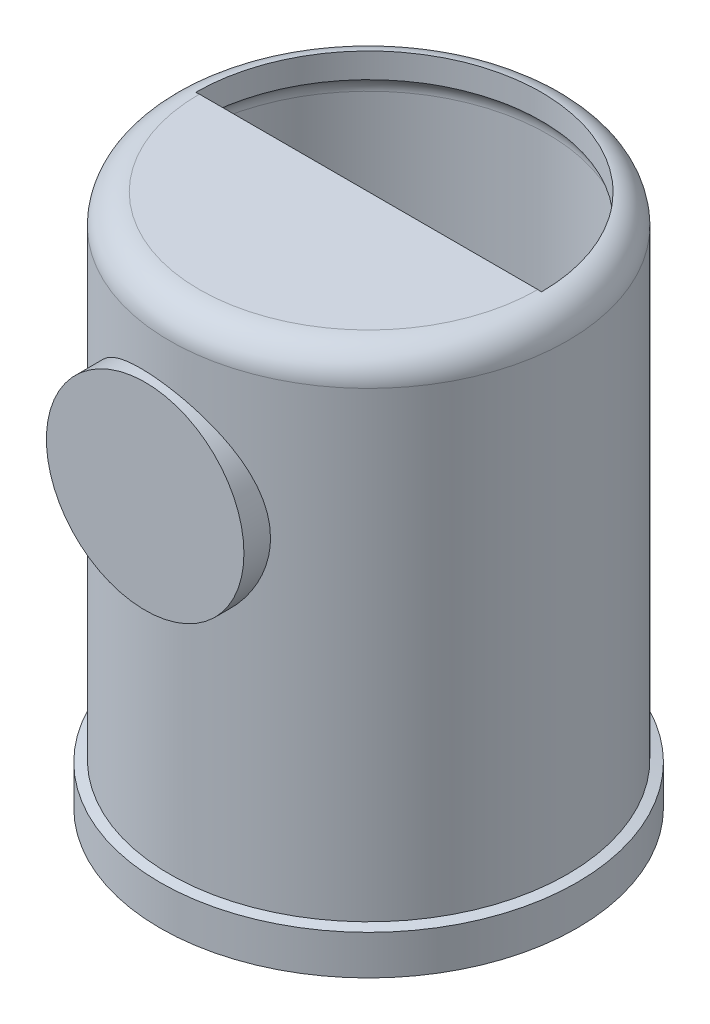
SolidWorks part; units mm, degrees
ref_plane "Front Plane" through (0, 0, 0) normal (0, 0, 1) x (1, 0, 0)
ref_plane "Top Plane" through (0, 0, 0) normal (0, 1, 0) x (1, 0, 0)
ref_plane "Right Plane" through (0, 0, 0) normal (1, 0, 0) x (0, 0, -1)
sketch "Sketch1" plane through (0, 0, 0) normal (0, 0, 1) x (1, 0, 0)
  line L0 (2.7649, 7.8218) -> (2.7649, 58.3592) construction
  line L1 (20.9, 0) -> (23.8716, 0)
  line L2 (23.8716, 0) -> (23.8716, 4)
  line L3 (23.8716, 4) -> (22.9, 4.2367)
  line L4 (22.9, 4.2367) -> (22.9, 51)
  line L6 (20.9, 0) -> (20.9, 15)
  line L7 (18.9, 52) -> (2.7649, 52)
  line L8 (2.7649, 52) -> (2.7649, 54)
  line L9 (20.9, 17) -> (20.9, 50)
  line L10 (20.9, 17) -> (2.7649, 17)
  line L12 (20.9, 15) -> (2.7649, 15)
  line L13 (2.7649, 17) -> (2.7649, 15)
  line L14 (19.9, 54) -> (2.7649, 54)
  arc A1 (20.9, 50) -> (18.9, 52) centre (18.9, 50) ccw
  arc A2 (22.9, 51) -> (19.9, 54) centre (19.9, 51) ccw
  point P11 (22.9, 54)
  dimension "D9" = 2
  dimension "D4" = 3
  dimension "D1" = 2
  dimension "D2" = 4
  dimension "D3" = 1
  dimension "D6" = 2
  dimension "D7" = 2.9716
  dimension "D10" = 2
  dimension "D11" = 15
  dimension "D12" = 35
  dimension "D13" = 37
revolve "Revolve1" add sketch "Sketch1" angle 360 about L0
ref_plane "Plane1" through (0, 4, 0) normal (0, 1, 0) x (1, 0, 0)
sketch "Sketch3" plane through (0, 0, 0) normal (0, 0, 1) x (1, 0, 0)
  point P0 (1.2404, 19.1989)
ref_point "Point1"
ref_plane "Plane2" through (0, 0, 21) normal (0, 0, 1) x (1, 0, 0)
sketch "Sketch4" plane through (0, 0, 21) normal (0, 0, 1) x (1, 0, 0)
  line L1 (22.9, 51) -> (-17.3702, 51) construction
  circle A1 centre (1.1446, 37) radius 10
  dimension "D1" = 20
  dimension "D2" = 14
extrude "Boss-Extrude2" add sketch "Sketch4" against normal blind 6
ref_plane "Plane3" through (0, 0, 15) normal (0, 0, -1) x (-1, 0, 0)
ref_plane "Plane4" through (0, 54, 0) normal (0, 1, 0) x (1, 0, 0)
sketch "Sketch9" plane through (0, 54, 0) normal (0, 1, 0) x (1, 0, 0)
  line L0 (-14.7351, -0.0013) -> (20.2649, -0.0013)
  arc A0 (20.2649, -0.0013) -> (-14.7351, -0.0013) centre (2.7649, -0.0013) ccw
  circle A1 centre (2.7649, 0) radius 17.1351 construction
  dimension "D1" = 35
  dimension "D3" = 17.5
  dimension "D2" = 17.5
extrude "Cut-Extrude2" cut sketch "Sketch9" against normal blind 40
